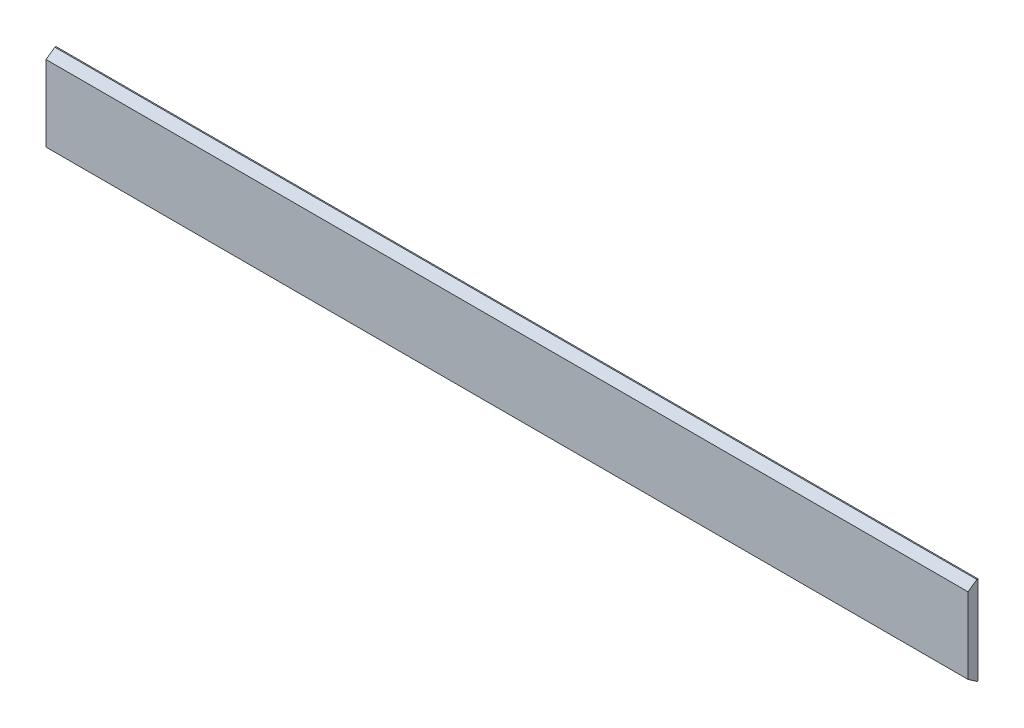
SolidWorks part; units mm, degrees
ref_plane "前视基准面" through (0, 0, 0) normal (0, 0, 1) x (1, 0, 0)
ref_plane "上视基准面" through (0, 0, 0) normal (0, 1, 0) x (1, 0, 0)
ref_plane "右视基准面" through (0, 0, 0) normal (1, 0, 0) x (0, 0, -1)
sketch "草图1" plane through (0, 0, 0) normal (0, 0, 1) x (1, 0, 0)
  line L1 (-830, 79.5) -> (830, 79.5)
  line L2 (-830, 79.5) -> (-830, -79.5)
  line L3 (-830, -79.5) -> (830, -79.5)
  line L4 (830, 79.5) -> (830, -79.5)
  line L5 (-830, 79.5) -> (830, -79.5) construction
  line L6 (-830, -79.5) -> (830, 79.5) construction
  point P0 (0, 0)
  dimension "D1" = 1660
  dimension "D2" = 159
extrude "凸台-拉伸1" add sketch "草图1" along normal blind 18
chamfer "倒角1" distance 16 angle 35 1 edges at (0, 79.5, 18)
chamfer "倒角2" distance 16 angle 35 1 edges at (0, -79.5, 18)
